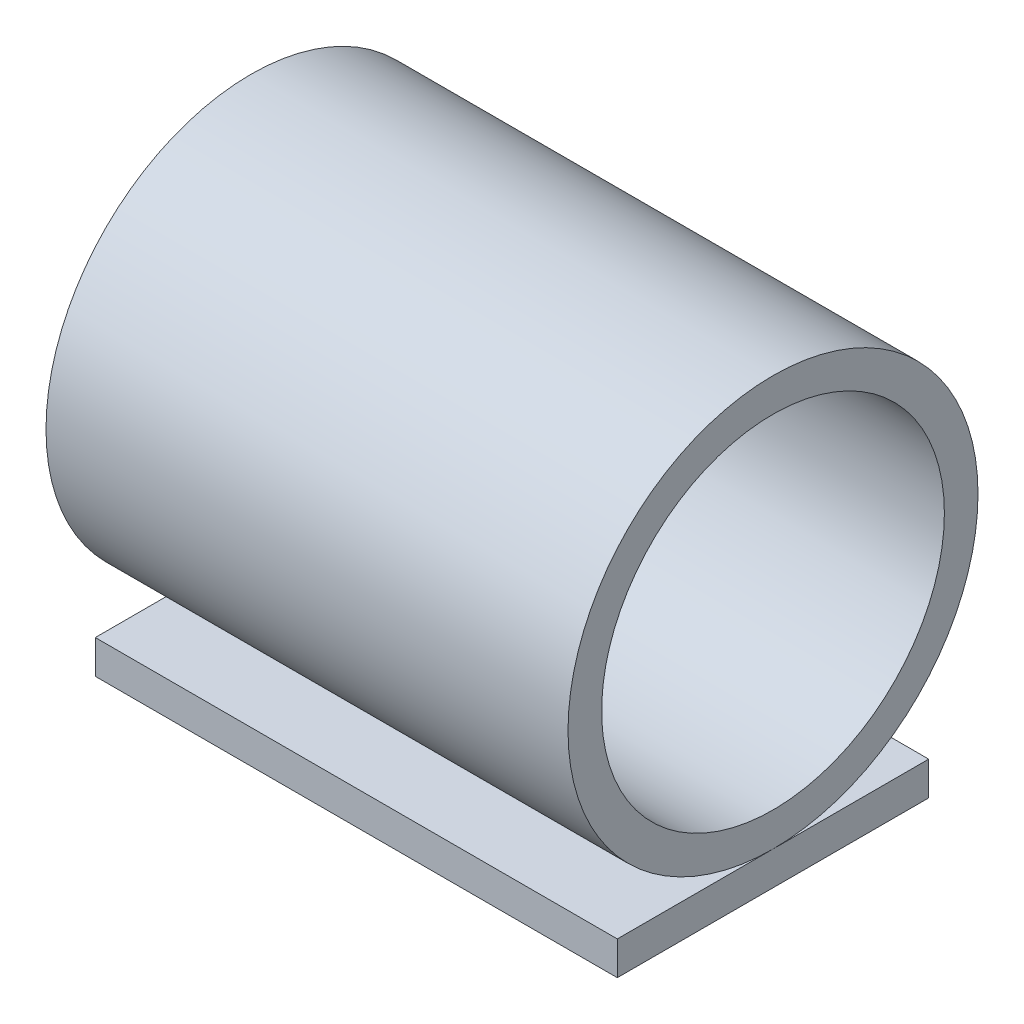
SolidWorks part; units mm, degrees
ref_plane "Front Plane" through (0, 0, 0) normal (0, 0, 1) x (1, 0, 0)
ref_plane "Top Plane" through (0, 0, 0) normal (0, 1, 0) x (1, 0, 0)
ref_plane "Right Plane" through (0, 0, 0) normal (1, 0, 0) x (0, 0, -1)
sketch "Sketch1" plane through (0, 0, 0) normal (0, 1, 0) x (1, 0, 0)
  line L1 (-46.6, 13.9) -> (0, 13.9)
  line L2 (-46.6, 13.9) -> (-46.6, -13.9)
  line L3 (-46.6, -13.9) -> (0, -13.9)
  line L4 (0, 13.9) -> (0, -13.9)
  dimension "D1" = 27.8
  dimension "D2" = 46.6
extrude "Boss-Extrude1" add sketch "Sketch1" along normal blind 3
sketch "Sketch3" plane through (0, 0, 0) normal (1, 0, 0) x (0, 0, -1)
  line L1 (-13.9, 3) -> (13.9, 3) construction
  line L2 (-13.9, 3) -> (-13.9, 0) construction
  circle A1 centre (0, 21.3) radius 18.3
  point P6 (-13.9, 1.5)
  dimension "D1" = 18.3
  dimension "D2" = 13.9
extrude "Boss-Extrude2" add sketch "Sketch3" against normal blind 46.6 separate body contours A1
sketch "Sketch4" plane through (0, 0, 0) normal (1, 0, 0) x (0, 0, -1)
  circle A0 centre (0, 21.3152) radius 15.3
extrude "Cut-Extrude1" cut sketch "Sketch4" against normal blind 46.6
